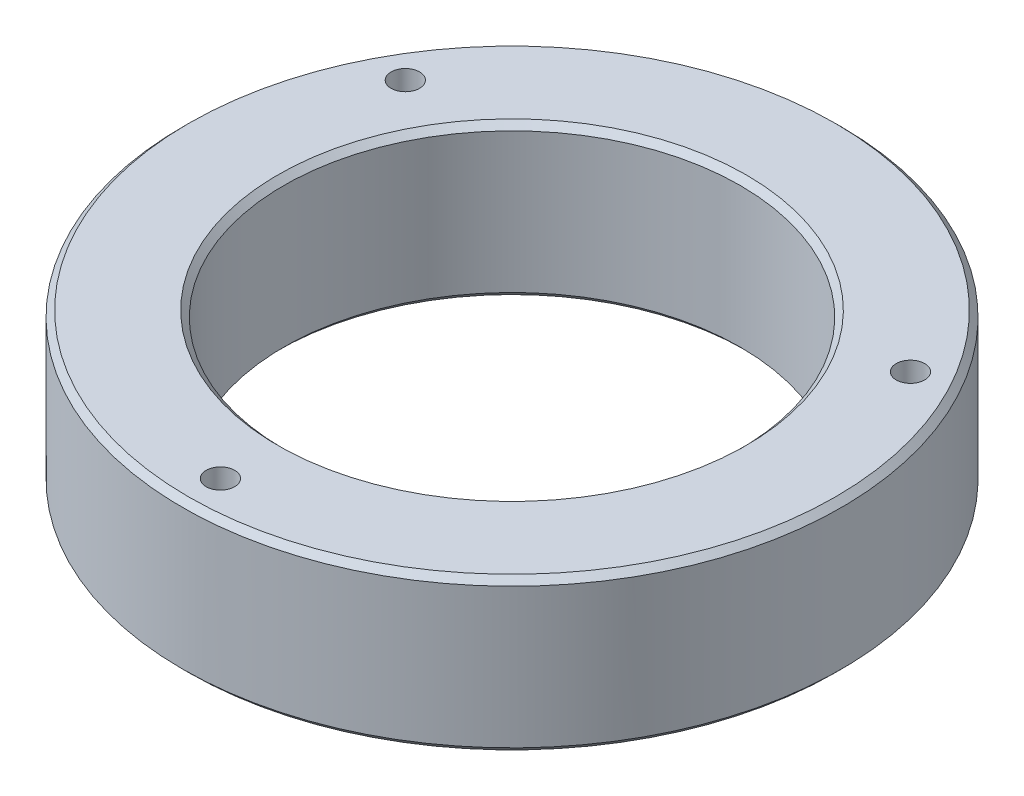
SolidWorks part; units mm, degrees
ref_plane "Front Plane" through (0, 0, 0) normal (1, 0, 0) x (0, 1, 0)
ref_plane "Top Plane" through (0, 0, 0) normal (0, 0, 1) x (0, 1, 0)
ref_plane "Right Plane" through (0, 0, 0) normal (0, 1, 0) x (-1, 0, 0)
sketch "Sketch1" plane through (0, 0, 0) normal (0, 0, 1) x (0, 1, 0)
  line L0 (-19.05, 82.5246) -> (19.05, 82.5246)
  line L1 (19.05, 82.5246) -> (19.05, 57.15)
  line L2 (19.05, 57.15) -> (-19.05, 57.15)
  line L3 (-19.05, 57.15) -> (-19.05, 82.5246)
  line L4 (-44.45, 0) -> (44.45, 0) construction
revolve "Revolve1" add sketch "Sketch1" angle 360 about L4
chamfer "Chamfer1" distance 1.524 angle 45 4 edges at (0, 19.05, -57.15) (0, -19.05, -57.15) (0, 19.05, -82.5246) (0, -19.05, -82.5246)
hole_wizard "CBORE for 1/4 Socket Head Cap Screw1" positions "Sketch3" profile "Sketch2" counterbore size "1/4" standard "ANSI Inch"
sketch "Sketch3" plane through (0, -19.05, 0) normal (0, -1, 0) x (-1, 0, 0)
  point P0 (0, -73.025)
  point P1 (-63.246, 36.5252)
  point P3 (63.246, 36.5252)
sketch "Sketch2" plane through (0, -19.05, 73.025) normal (1, 0, 0) x (0, 0, -1)
  line L0 (0, 0) -> (0, 40.2443)
  line L1 (0, 40.2443) -> (3.5687, 38.1)
  line L2 (3.5687, 38.1) -> (3.5687, 9.652)
  line L3 (3.5687, 9.652) -> (5.5626, 9.652)
  line L4 (5.5626, 9.652) -> (5.5626, 0)
  line L5 (5.5626, 0) -> (0, 0)
  line L10 (0, 40.2443) -> (-3.5687, 38.1) construction
  line L11 (0, -6.35) -> (0, 107.95) construction
  dimension "Hole Dia." = 7.1374
  dimension "Hole Depth" = 38.1
  dimension "C'Bore Dia." = 11.1252
  dimension "C'Bore Depth" = 9.652
  dimension "Drill Angle" = 118
hole_wizard "3/8-16 Tapped Hole2" positions "Sketch7" profile "Sketch6" tap size "3/8-16" standard "ANSI Inch"
sketch "Sketch7" plane through (0, -19.05, 0) normal (0, -1, 0) x (-1, 0, 0)
  point P0 (-69.85, 0)
  point P1 (69.85, 0)
sketch "Sketch6" plane through (69.85, -19.05, 0) normal (1, 0, 0) x (0, 0, -1)
  line L0 (0, 0) -> (0, 27.7847)
  line L1 (0, 27.7847) -> (3.9687, 25.4)
  line L2 (3.9687, 25.4) -> (3.9687, 0)
  line L5 (3.9687, 0) -> (0, 0)
  line L10 (0, 27.7847) -> (-3.9687, 25.4) construction
  line L11 (0, -6.35) -> (0, 107.95) construction
  dimension "Tap Drill Dia." = 7.9375
  dimension "Tap Drill Depth" = 25.4
  dimension "Drill Angle" = 118
cosmetic thread "Hole Thread3"
cosmetic thread "Hole Thread4"
